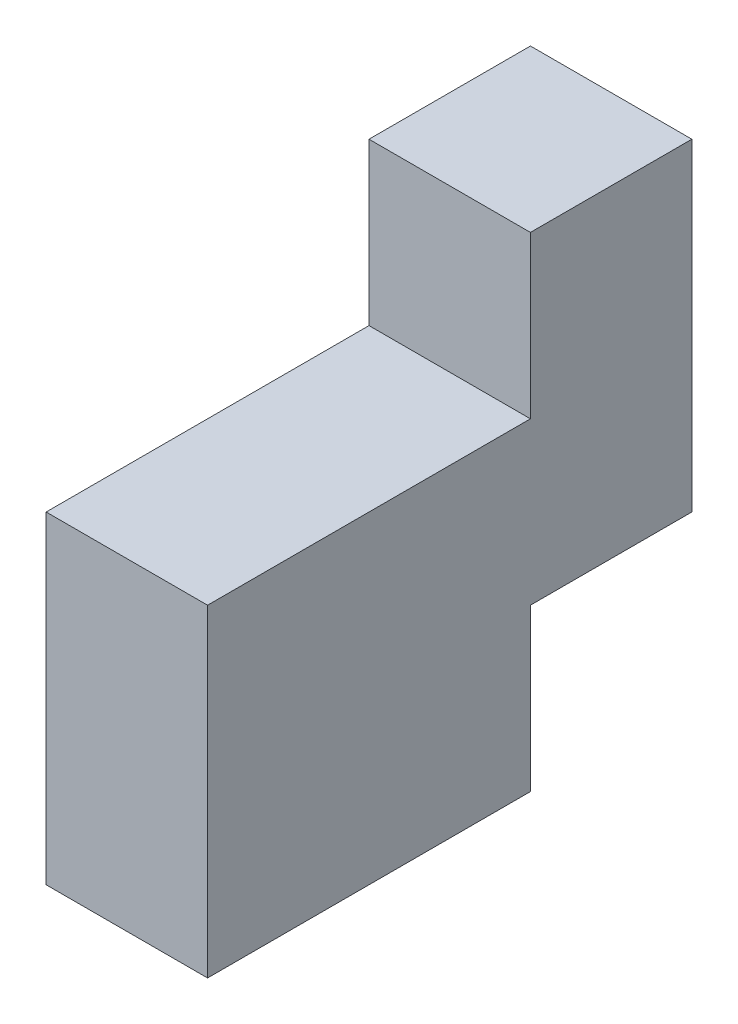
SolidWorks part; units mm, degrees
ref_plane "Front Plane" through (0, 0, 0) normal (0, 0, 1) x (1, 0, 0)
ref_plane "Top Plane" through (0, 0, 0) normal (0, 1, 0) x (1, 0, 0)
ref_plane "Right Plane" through (0, 0, 0) normal (1, 0, 0) x (0, 0, -1)
sketch "Sketch1" plane through (0, 0, 0) normal (0, 1, 0) x (1, 0, 0)
  line L1 (0, 0) -> (25.4, 0)
  line L2 (0, 0) -> (0, -76.2)
  line L3 (0, -76.2) -> (25.4, -76.2)
  line L4 (25.4, 0) -> (25.4, -76.2)
  dimension "D1" = 25.4
  dimension "D2" = 76.2
extrude "Boss-Extrude3" add sketch "Sketch1" along normal blind 25.4
sketch "Sketch3" plane through (0, 25.4, 0) normal (0, 1, 0) x (1, 0, 0)
  line L1 (0, 0) -> (25.4, 0)
  line L2 (0, 0) -> (0, -25.4)
  line L3 (0, -25.4) -> (25.4, -25.4)
  line L4 (25.4, 0) -> (25.4, -25.4)
  dimension "D1" = 25.4
  dimension "D2" = 25.4
extrude "Boss-Extrude4" add sketch "Sketch3" along normal blind 25.4
sketch "Sketch5" plane through (0, 0, 0) normal (0, -1, 0) x (-1, 0, 0)
  line L0 (-25.4, -76.2) -> (-25.4, 0) construction
  line L1 (0, -76.2) -> (-25.4, -76.2)
  line L2 (0, -76.2) -> (0, -50.8)
  line L3 (0, -50.8) -> (-25.4, -50.8)
  line L4 (-25.4, -76.2) -> (-25.4, -50.8)
  dimension "D1" = 25.4
extrude "Boss-Extrude5" add sketch "Sketch5" along normal blind 25.4
sketch "Sketch7" plane through (0, 0, 50.8) normal (0, 0, -1) x (-1, 0, 0)
  line L1 (-25.4, 0) -> (0, 0)
  line L2 (-25.4, 0) -> (-25.4, -25.4)
  line L3 (-25.4, -25.4) -> (0, -25.4)
  line L4 (0, 0) -> (0, -25.4)
extrude "Boss-Extrude6" add sketch "Sketch7" along normal blind 25.4
